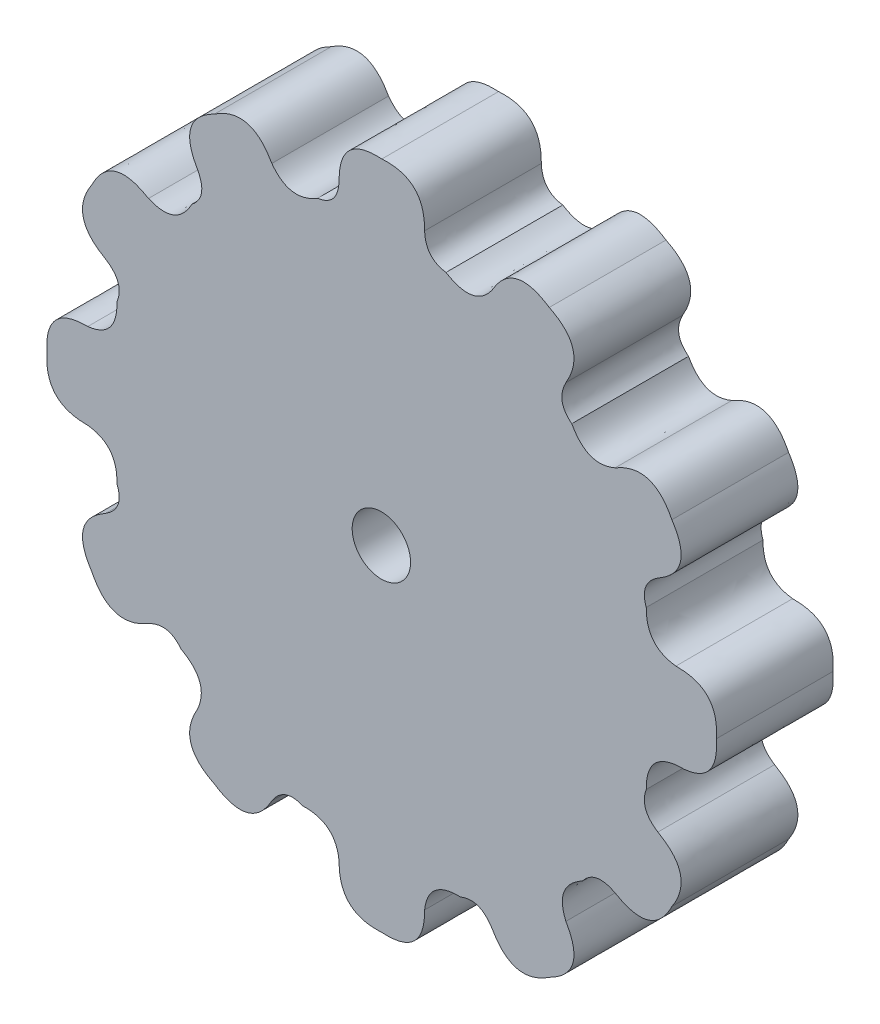
SolidWorks part; units mm, degrees
ref_plane "Front Plane" through (0, 0, 0) normal (0, 0, 1) x (1, 0, 0)
ref_plane "Top Plane" through (0, 0, 0) normal (0, 1, 0) x (1, 0, 0)
ref_plane "Right Plane" through (0, 0, 0) normal (1, 0, 0) x (0, 0, -1)
sketch "Sketch1" plane through (0, 0, 0) normal (0, 0, 1) x (1, 0, 0)
  line L0 (22.6913, 6.75) -> (22.6913, -6.75) construction
  line L2 (0, 0) -> (25.1913, 6.75) construction
  line L3 (0, 6.75) -> (25.1913, 6.75) construction
  line L4 (25.1913, 6.75) -> (25.1913, -6.75) construction
  line L6 (22.6913, 0) -> (28.6913, 0) construction
  circle A0 centre (25.1913, 6.75) radius 2.5
  circle A1 centre (25.1913, -6.75) radius 2.5
  spline S0 degree 2 poles (25.2292, 3.6657) (28.97, 3.7139) (28.6913, 0) knots 0 0 0 1 1 1
  spline S1 degree 2 poles (25.2292, 3.6657) (22.6642, 3.966) (22.6913, 6.75) knots 0 0 0 1 1 1
  spline S2 degree 2 poles (25.2292, -3.6657) (22.6642, -3.966) (22.6913, -6.75) knots 0 0 0 1 1 1
  spline S3 degree 2 poles (25.2292, -3.6657) (28.97, -3.7139) (28.6913, 0) knots 0 0 0 1 1 1
  spline S4 degree 2 poles (20.0214, -15.7702) (23.2285, -17.6703) (24.8853, -14.3457) knots 0 0 0 1 1 1
  spline S5 degree 2 poles (20.0214, -15.7702) (18.3242, -14.8762) (17.2292, -16.2763) knots 0 0 0 1 1 1
  spline S6 degree 2 poles (23.6871, -9.4211) (22.0928, -8.4032) (22.6913, -6.75) knots 0 0 0 1 1 1
  spline S7 degree 2 poles (23.6871, -9.4211) (26.9361, -11.2485) (24.8853, -14.3457) knots 0 0 0 1 1 1
  spline S8 degree 2 poles (9.459, -23.6492) (11.2864, -26.8982) (14.3835, -24.8474) knots 0 0 0 1 1 1
  spline S9 degree 2 poles (9.459, -23.6492) (8.4362, -22.0264) (6.7879, -22.6913) knots 0 0 0 1 1 1
  spline S10 degree 2 poles (15.8081, -19.9835) (14.7769, -17.6098) (17.2292, -16.2763) knots 0 0 0 1 1 1
  spline S11 degree 2 poles (15.8081, -19.9835) (17.7082, -23.1906) (14.3835, -24.8474) knots 0 0 0 1 1 1
  spline S12 degree 2 poles (-3.6278, -25.1913) (-3.6698, -28.9188) (0.0379, -28.6913) knots 0 0 0 1 1 1
  spline S13 degree 2 poles (-3.6278, -25.1913) (-3.9216, -22.62) (-6.7121, -22.6913) knots 0 0 0 1 1 1
  spline S14 degree 2 poles (3.7035, -25.1913) (3.9974, -22.62) (6.7879, -22.6913) knots 0 0 0 1 1 1
  spline S15 degree 2 poles (3.7035, -25.1913) (3.7455, -28.9188) (0.0379, -28.6913) knots 0 0 0 1 1 1
  spline S16 degree 2 poles (-15.7324, -19.9835) (-17.6324, -23.1906) (-14.3078, -24.8474) knots 0 0 0 1 1 1
  spline S17 degree 2 poles (-15.7324, -19.9835) (-14.7012, -17.6098) (-17.1535, -16.2763) knots 0 0 0 1 1 1
  spline S18 degree 2 poles (-9.3832, -23.6492) (-8.3605, -22.0264) (-6.7121, -22.6913) knots 0 0 0 1 1 1
  spline S19 degree 2 poles (-9.3832, -23.6492) (-11.2106, -26.8982) (-14.3078, -24.8474) knots 0 0 0 1 1 1
  spline S20 degree 2 poles (-23.6113, -9.4211) (-26.8603, -11.2485) (-24.8096, -14.3457) knots 0 0 0 1 1 1
  spline S21 degree 2 poles (-23.6113, -9.4211) (-21.9885, -8.3983) (-22.6535, -6.75) knots 0 0 0 1 1 1
  spline S22 degree 2 poles (-19.9456, -15.7702) (-18.2485, -14.8762) (-17.1535, -16.2763) knots 0 0 0 1 1 1
  spline S23 degree 2 poles (-19.9456, -15.7702) (-23.1527, -17.6703) (-24.8096, -14.3457) knots 0 0 0 1 1 1
  spline S24 degree 2 poles (-25.1535, 3.6657) (-28.8809, 3.7076) (-28.6535, 0) knots 0 0 0 1 1 1
  spline S25 degree 2 poles (-25.1535, 3.6657) (-22.5822, 3.9595) (-22.6535, 6.75) knots 0 0 0 1 1 1
  spline S26 degree 2 poles (-25.1535, -3.6657) (-22.5822, -3.9595) (-22.6535, -6.75) knots 0 0 0 1 1 1
  spline S27 degree 2 poles (-25.1535, -3.6657) (-28.8809, -3.7076) (-28.6535, 0) knots 0 0 0 1 1 1
  spline S28 degree 2 poles (-19.9456, 15.7702) (-23.1527, 17.6703) (-24.8096, 14.3457) knots 0 0 0 1 1 1
  spline S29 degree 2 poles (-19.9456, 15.7702) (-17.5719, 14.7391) (-16.2384, 17.1913) knots 0 0 0 1 1 1
  spline S30 degree 2 poles (-23.6113, 9.4211) (-21.9885, 8.3983) (-22.6535, 6.75) knots 0 0 0 1 1 1
  spline S31 degree 2 poles (-23.6113, 9.4211) (-26.8603, 11.2485) (-24.8096, 14.3457) knots 0 0 0 1 1 1
  spline S32 degree 2 poles (-9.3832, 23.6492) (-11.2106, 26.8982) (-14.3078, 24.8474) knots 0 0 0 1 1 1
  spline S33 degree 2 poles (-9.3832, 23.6492) (-7.8431, 21.5693) (-5.4621, 23.0263) knots 0 0 0 1 1 1
  spline S34 degree 2 poles (-15.7324, 19.9835) (-14.8383, 18.2864) (-16.2384, 17.1913) knots 0 0 0 1 1 1
  spline S35 degree 2 poles (-15.7324, 19.9835) (-17.6324, 23.1906) (-14.3078, 24.8474) knots 0 0 0 1 1 1
  spline S36 degree 2 poles (3.7035, 25.1913) (3.7455, 28.9188) (0.0379, 28.6913) knots 0 0 0 1 1 1
  spline S37 degree 2 poles (3.7035, 25.1913) (3.7779, 23.2746) (5.5379, 23.0263) knots 0 0 0 1 1 1
  spline S38 degree 2 poles (-3.6278, 25.1913) (-3.7021, 23.2746) (-5.4621, 23.0263) knots 0 0 0 1 1 1
  spline S39 degree 2 poles (-3.6278, 25.1913) (-3.6698, 28.9188) (0.0379, 28.6913) knots 0 0 0 1 1 1
  spline S40 degree 2 poles (15.8081, 19.9835) (17.7082, 23.1906) (14.3835, 24.8474) knots 0 0 0 1 1 1
  spline S41 degree 2 poles (15.8081, 19.9835) (14.9141, 18.2864) (16.3142, 17.1913) knots 0 0 0 1 1 1
  spline S42 degree 2 poles (9.459, 23.6492) (7.9188, 21.5693) (5.5379, 23.0263) knots 0 0 0 1 1 1
  spline S43 degree 2 poles (9.459, 23.6492) (11.2864, 26.8982) (14.3835, 24.8474) knots 0 0 0 1 1 1
  spline S44 degree 2 poles (23.6871, 9.4211) (26.9361, 11.2485) (24.8853, 14.3457) knots 0 0 0 1 1 1
  spline S45 degree 2 poles (23.6871, 9.4211) (22.0928, 8.4032) (22.6913, 6.75) knots 0 0 0 1 1 1
  spline S46 degree 2 poles (20.0214, 15.7702) (17.6476, 14.7391) (16.3142, 17.1913) knots 0 0 0 1 1 1
  spline S47 degree 2 poles (20.0214, 15.7702) (23.2285, 17.6703) (24.8853, 14.3457) knots 0 0 0 1 1 1
  point P4 (5.2051, 23.0263)
  point P16 (22.6925, -6.826)
  point P19 (16.3594, 17.0436)
  point P21 (0, 0)
  point P30 (0, 0)
  point P46 (0, 0)
  point P55 (0, 0)
  point P57 (-22.6913, 7.1095)
  point P73 (-16.5107, 16.7993)
  point P82 (-5.5, 22.8189)
  point P93 (22.7006, 6.5347)
  point P102 (0, 0)
  point P111 (-22.6913, 6.4561)
  dimension "D3" = 5
  dimension "D1" = 6.75
  dimension "D4" = 13.5
  dimension "D6" = 6
extrude "Boss-Extrude1" add sketch "Sketch1" along normal blind 10 contours S47 S46 S41 S40 S43 S42 S37 S36 S39 S38 S33 S32 S35 S34 S29 S28 S31 S30 S25 S24 S27 S26 S21 S20 S23 S22 S17 S16 S19 S18 S13 S12 S15 S14 S9 S8 S11 S10 S5 S4 S7 S6 S2 S3 S0 S1 S45 S44
sketch "Sketch2" plane through (0, 0, 10) normal (0, 0, 1) x (1, 0, 0)
  circle A0 centre (0, 0) radius 2.5
  dimension "D1" = 5
extrude "Cut-Extrude1" cut sketch "Sketch2" against normal blind 10
